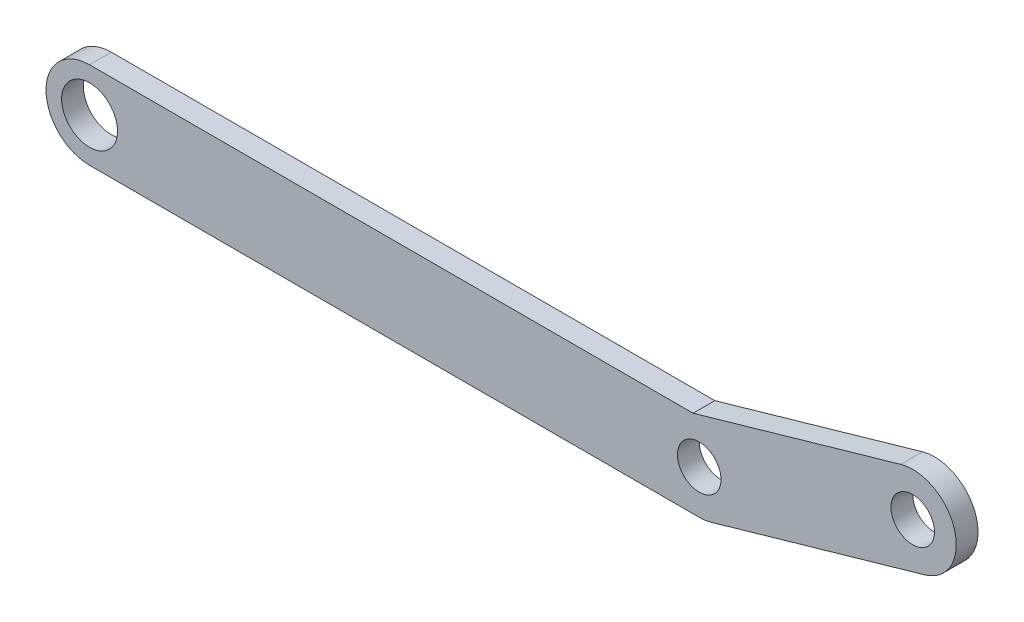
SolidWorks part; units mm, degrees
ref_plane "Alzado" through (0, 0, 0) normal (0, 0, 1) x (1, 0, 0)
ref_plane "Planta" through (0, 0, 0) normal (0, 1, 0) x (1, 0, 0)
ref_plane "Vista lateral" through (0, 0, 0) normal (1, 0, 0) x (0, 0, -1)
sketch "Croquis1" plane through (0, 0, 0) normal (0, 0, 1) x (1, 0, 0)
  line L0 (-70, 0) -> (70, 0) construction
  line L3 (-70, 10) -> (68.5946, 10)
  line L6 (-70, -10) -> (70, -10)
  line L7 (70, 0) -> (119.0243, 14.0575) construction
  line L8 (68.5946, 10) -> (116.268, 23.6701)
  line L9 (72.7564, -9.6126) -> (121.7807, 4.4449)
  arc A6 (-70, 10) -> (-70, -10) centre (-70, 0) ccw
  circle A8 centre (70, 0) radius 5
  arc A10 (121.7807, 4.4449) -> (116.268, 23.6701) centre (119.0243, 14.0575) ccw
  circle A11 centre (119.0243, 14.0575) radius 5
  arc A12 (72.7564, -9.6126) -> (70, -10) centre (70, 0) cw
  circle A13 centre (-70, 0) radius 6.4174
  point P2 (0, 0)
  point P10 (94.5122, 7.0288)
  dimension "D2" = 20
  dimension "D3" = 10
  dimension "D7" = 10
  dimension "D1" = 140
  dimension "D4" = 20
  dimension "D5" = 51
  dimension "D6" = 16
extrude "Saliente-Extruir1" add sketch "Croquis1" along normal blind 5
equation "\"largo\"= 140"
